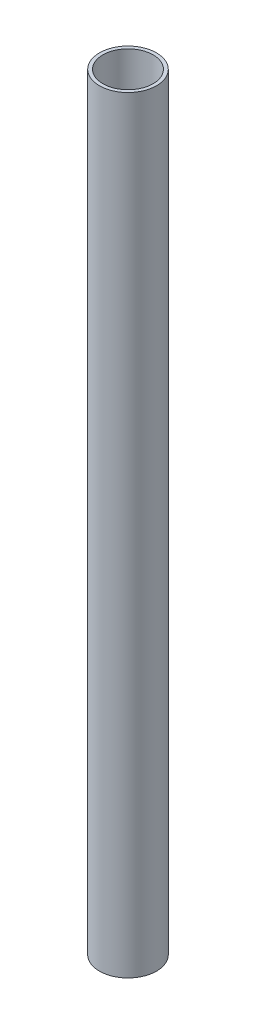
SolidWorks part; units mm, degrees
material "Zoltek Panex 33"
ref_plane "Front Plane" through (0, 0, 0) normal (0, 0, 1) x (1, 0, 0)
ref_plane "Top Plane" through (0, 0, 0) normal (0, 1, 0) x (1, 0, 0)
ref_plane "Right Plane" through (0, 0, 0) normal (1, 0, 0) x (0, 0, -1)
sketch "Sketch1" plane through (0, 0, 0) normal (0, 1, 0) x (1, 0, 0)
  circle A0 centre (0, 0) radius 12.5
  circle A1 centre (0, 0) radius 11
  dimension "D1" = 25
  dimension "D2" = 22
extrude "Boss-Extrude1" add sketch "Sketch1" along normal blind 336.16
